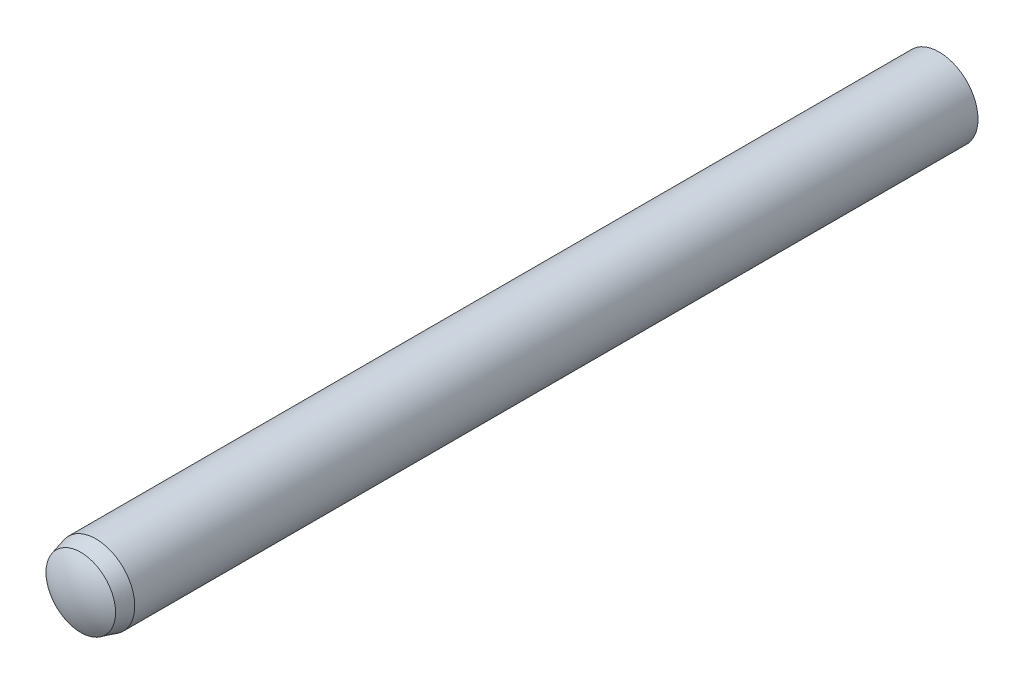
SolidWorks part; units mm, degrees
ref_plane "Front Plane" through (0, 0, 0) normal (0, 0, 1) x (1, 0, 0)
ref_plane "Top Plane" through (0, 0, 0) normal (0, 1, 0) x (1, 0, 0)
ref_plane "Right Plane" through (0, 0, 0) normal (1, 0, 0) x (0, 0, -1)
sketch "Sketch1" plane through (0, 0, 0) normal (0, 0, 1) x (1, 0, 0)
  circle A0 centre (0, 0) radius 1.5
  point P3 (0, 1.5)
  dimension "Diameter" = 3
sketch "Sketch2" plane through (0, 0, 0) normal (1, 0, 0) x (0, 0, -1)
  line L0 (-17, 0) -> (17, 0) construction
  line L1 (-17, 0) -> (-17, 1.5) construction
  line L2 (-17, 1.5) -> (17, 1.5)
  line L3 (17, 1.5) -> (17, 0) construction
  line L4 (-16.61, 1.3432) -> (-16.025, 1.5)
  arc A0 (-17, 0) -> (-16.61, 1.3432) centre (-14.4918, 0) cw
  arc A1 (17, 0) -> (16.55, 1.5) centre (14.275, 0) ccw
  point P2 (0, 0)
  point P11 (-14, 0)
  point P13 (14, 0)
  dimension "Length" = 34
  dimension "D1" = 15
  dimension "D2" = 0.45
  dimension "D3" = 0.975
  dimension "D4" = 0.585
  dimension "D5" = 3
  dimension "D6" = 3
sketch "Sketch3" plane through (0, 0, 0) normal (1, 0, 0) x (0, 0, -1)
  line L0 (-17, 0) -> (17, 0) construction
  line L1 (-16.61, 1.3432) -> (-16.025, 1.5) construction
  line L2 (-17, 0) -> (17, 0)
  line L3 (-16.61, 1.3432) -> (-16.025, 1.5)
  line L4 (-16.025, 1.5) -> (16.55, 1.5)
  arc A0 (17, 0) -> (16.55, 1.5) centre (14.275, 0) ccw construction
  arc A1 (-16.61, 1.3432) -> (-17, 0) centre (-14.4918, 0) ccw construction
  arc A2 (17, 0) -> (16.55, 1.5) centre (14.275, 0) ccw
  arc A3 (-16.61, 1.3432) -> (-17, 0) centre (-14.4918, 0) ccw
revolve "Revolve1" add sketch "Sketch3" angle 360 about L2
equation "\"D2@Sketch2\" = \"Diameter@Sketch1\" * .15"
equation "\"D3@Sketch2\" = \"Diameter@Sketch1\" * .325"
equation "\"D4@Sketch2\" = \"D3@Sketch2\" * .6"
equation "\"D5@Sketch2\"=\"Diameter@Sketch1\""
equation "\"D6@Sketch2\"=\"D5@sketch2\""
